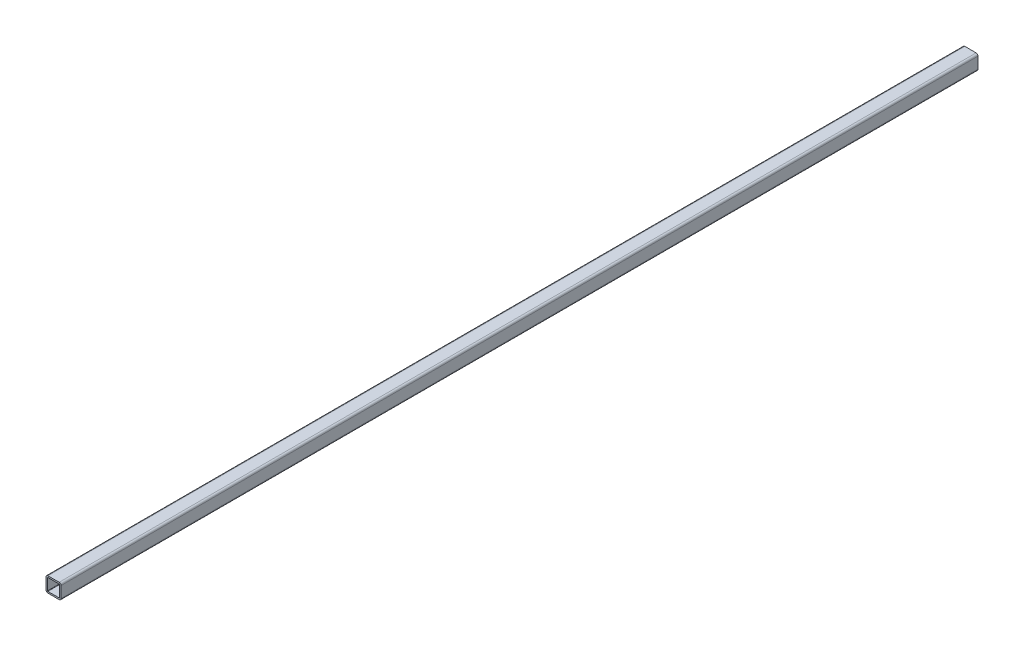
SolidWorks part; units mm, degrees
ref_plane "Front Plane" through (0, 0, 0) normal (0, 0, 1) x (1, 0, 0)
ref_plane "Top Plane" through (0, 0, 0) normal (0, 1, 0) x (1, 0, 0)
ref_plane "Right Plane" through (0, 0, 0) normal (1, 0, 0) x (0, 0, -1)
sketch "Sketch1" plane through (0, 0, 0) normal (0, 0, 1) x (1, 0, 0)
  line L1 (7.5, -10) -> (-7.5, -10)
  line L2 (10, -7.5) -> (10, 7.5)
  line L3 (7.5, 10) -> (-7.5, 10)
  line L4 (-10, -7.5) -> (-10, 7.5)
  line L5 (10, -10) -> (-10, 10) construction
  line L6 (10, 10) -> (-10, -10) construction
  arc A0 (-7.5, 10) -> (-10, 7.5) centre (-7.5, 7.5) ccw
  arc A1 (10, 7.5) -> (7.5, 10) centre (7.5, 7.5) ccw
  arc A2 (7.5, -10) -> (10, -7.5) centre (7.5, -7.5) ccw
  arc A3 (-7.5, -10) -> (-10, -7.5) centre (-7.5, -7.5) cw
  point P0 (0, 0)
  dimension "D2" = 2.5
  dimension "D1" = 20
extrude "Extrude-Thin1" add sketch "Sketch1" along normal mid plane 1219.2 thin
equation "\"D2@Sketch1\" = \"D5@Extrude-Thin1\" * 1.25"
